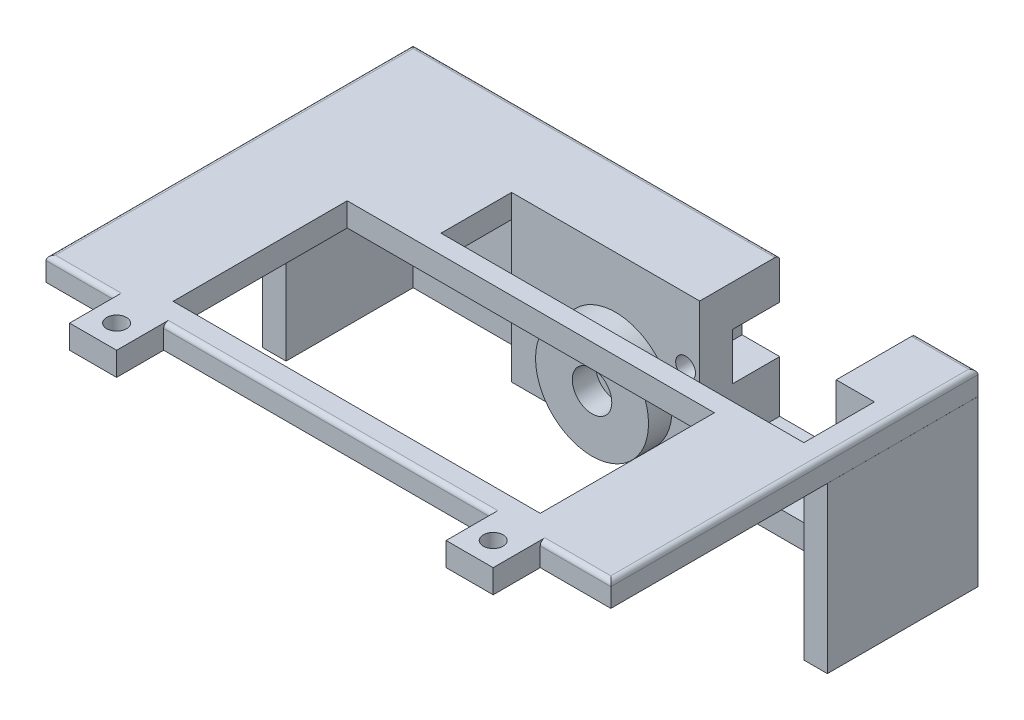
SolidWorks part; units mm, degrees
ref_plane "Спереди" through (0, 0, 0) normal (0, 0, 1) x (1, 0, 0)
ref_plane "Сверху" through (0, 0, 0) normal (0, 1, 0) x (1, 0, 0)
ref_plane "Справа" through (0, 0, 0) normal (1, 0, 0) x (0, 0, -1)
ref_plane "Плоскость4" through (0, 0, 54.0527) normal (0, 0, -1) x (-1, 0, 0)
sketch "Эскиз1" plane through (0, 0, 54.0527) normal (0, 0, -1) x (-1, 0, 0)
  circle A0 centre (-68.7418, 84.0014) radius 4.2
  circle A1 centre (-68.7418, 84.0014) radius 12
extrude "Бобышка-Вытянуть1" add sketch "Эскиз1" along normal blind 5
ref_plane "Плоскость5" through (0, 0, 49.0527) normal (0, 0, -1) x (-1, 0, 0)
sketch "Эскиз2" plane through (0, 0, 49.0527) normal (0, 0, -1) x (-1, 0, 0)
  line L0 (-115.6175, 77.2768) -> (-86.6175, 77.2768)
  line L1 (-86.6175, 93.2768) -> (-86.6175, 102.0014)
  line L2 (-128.7418, 102.0014) -> (-8.7418, 102.0014) construction
  line L3 (-115.6175, 93.2768) -> (-115.6175, 77.2768)
  line L4 (-46.6175, 102.0014) -> (-46.6175, 57.1014)
  line L5 (-86.6175, 93.2768) -> (-86.6175, 77.2768)
  line L6 (-53.8918, 57.1014) -> (-83.5918, 57.1014) construction
  line L7 (-115.6175, 93.2768) -> (-115.6175, 102.0014)
  line L8 (-115.6175, 102.0014) -> (-123.7418, 102.0014)
  line L9 (-86.6175, 102.0014) -> (-46.6175, 102.0014)
  line L10 (-123.7418, 57.1014) -> (-46.6175, 57.1014)
  line L14 (-123.7418, 102.0014) -> (-123.7418, 57.1014)
  line L15 (-123.7418, 67.1014) -> (-123.7418, 57.1014) construction
  circle A0 centre (-118.6175, 93.2768) radius 2
  circle A1 centre (-83.6175, 93.2768) radius 2
extrude "Бобышка-Вытянуть2" add sketch "Эскиз2" along normal blind 5
ref_plane "Плоскость6" through (0, 0, 44.0527) normal (0, 0, -1) x (-1, 0, 0)
sketch "Эскиз3" plane through (0, 0, 44.0527) normal (0, 0, -1) x (-1, 0, 0)
  line L0 (-123.7418, 57.1014) -> (-123.7418, 72.0014)
  line L1 (-123.7418, 102.0014) -> (-123.7418, 57.1014) construction
  line L3 (-123.7418, 72.0014) -> (-46.6175, 72.0014)
  line L4 (-46.6175, 57.1014) -> (-46.6175, 102.0014) construction
  line L5 (-46.6175, 72.0014) -> (-46.6175, 57.1014)
  line L6 (-46.6175, 57.1014) -> (-123.7418, 57.1014)
extrude "Бобышка-Вытянуть3" add sketch "Эскиз3" along normal blind 7
ref_plane "Плоскость8" through (0, 72.0014, 0) normal (0, 1, 0) x (1, 0, 0)
sketch "Эскиз4" plane through (0, 72.0014, 0) normal (0, 1, 0) x (1, 0, 0)
  line L0 (123.7418, -37.0527) -> (13.7418, -37.0527)
  line L1 (13.7418, -37.0527) -> (13.7418, -59.0527)
  line L5 (13.7418, -59.0527) -> (8.7418, -59.0527)
  line L10 (8.7418, -59.0527) -> (8.7418, -32.0527)
  line L12 (128.7418, -17.0527) -> (128.7418, -64.0527) construction
  line L13 (128.7418, -32.0527) -> (128.7418, -59.0527)
  line L14 (128.7418, -59.0527) -> (123.7418, -59.0527)
  line L15 (123.7418, -59.0527) -> (123.7418, -37.0527)
  line L16 (8.7418, -32.0527) -> (128.7418, -32.0527)
extrude "Бобышка-Вытянуть6" add sketch "Эскиз4" along normal blind 30 separate body
sketch "Эскиз5" plane through (0, 0, 44.0527) normal (0, 0, -1) x (-1, 0, 0)
  line L0 (-115.6175, 102.0014) -> (-115.6175, 77.2768)
  line L1 (-115.6175, 77.2768) -> (-115.6175, 102.0014) construction
  line L2 (-115.6175, 77.2768) -> (-86.6175, 77.2768)
  line L3 (-86.6175, 77.2768) -> (-86.6175, 102.0014)
  line L4 (-86.6175, 102.0014) -> (-86.6175, 77.2768) construction
  line L5 (-115.6175, 102.0014) -> (-86.6175, 102.0014)
extrude "Вырез-Вытянуть16" cut sketch "Эскиз5" along normal blind 30
sketch "Эскиз6" plane through (0, 72.0014, 0) normal (0, 1, 0) x (1, 0, 0)
  line L0 (23.7418, -22.0527) -> (33.7418, -22.0527)
  line L1 (33.7418, -22.0527) -> (33.7418, -32.0527)
  line L4 (33.7418, -32.0527) -> (23.7418, -32.0527)
  line L5 (23.7418, -32.0527) -> (23.7418, -22.0527)
  line L6 (103.7418, -22.0527) -> (113.7418, -22.0527)
  line L7 (113.7418, -22.0527) -> (113.7418, -32.0527)
  line L10 (113.7418, -32.0527) -> (103.7418, -32.0527)
  line L11 (103.7418, -32.0527) -> (103.7418, -22.0527)
  circle A0 centre (28.7418, -27.0527) radius 2.1
  circle A1 centre (108.7418, -27.0527) radius 2.1
  point P2 (0, 0)
  point P3 (0, 0)
  point P6 (0, 0)
  point P7 (0, 0)
  point P8 (0, 0)
  point P9 (0, 0)
  point P11 (0, 0)
  point P13 (0, 0)
  point P14 (0, 0)
  point P17 (0, 0)
  point P18 (0, 0)
  point P22 (0, 0)
ref_plane "Плоскость9" through (0, 72.0014, 0) normal (0, 1, 0) x (1, 0, 0)
sketch "Эскиз7" plane through (0, 72.0014, 0) normal (0, 1, 0) x (1, 0, 0)
  line L0 (123.7418, -44.0527) -> (115.6175, -44.0527)
  line L1 (16.5, -44.0527) -> (-16.5, -44.0527) construction
  line L2 (115.6175, -37.0527) -> (123.7418, -37.0527)
  line L3 (123.7418, -37.0527) -> (123.7418, -44.0527)
  line L4 (123.7418, -37.0527) -> (123.7418, -59.0527) construction
  line L5 (115.6175, -44.0527) -> (115.6175, -37.0527)
  line L6 (86.6175, -37.0527) -> (86.6175, -44.0527)
  line L7 (86.6175, -32.0527) -> (86.6175, -37.0527) construction
  line L8 (13.7418, -37.0527) -> (86.6175, -37.0527) construction
  line L9 (86.6175, -44.0527) -> (46.6175, -44.0527)
  line L10 (46.6175, -44.0527) -> (46.6175, -49.0527) construction
  line L11 (46.6175, -44.0527) -> (46.6175, -37.0527)
  line L12 (46.6175, -37.0527) -> (86.6175, -37.0527)
sketch "Эскиз8" plane through (0, 72.0014, 0) normal (0, 1, 0) x (1, 0, 0)
  line L0 (86.6175, -37.0527) -> (86.6175, -44.0527)
  line L1 (16.5, -44.0527) -> (-16.5, -44.0527) construction
  line L2 (86.6175, -44.0527) -> (115.6175, -44.0527)
  line L3 (115.6175, -44.0527) -> (115.6175, -37.0527)
  line L4 (115.6175, -37.0527) -> (86.6175, -37.0527)
sketch "Эскиз9" plane through (0, 0, 49.0527) normal (0, 0, -1) x (-1, 0, 0)
  circle A0 centre (-83.6175, 93.2768) radius 2.1
  circle A1 centre (-118.6175, 93.2768) radius 2
extrude "Вырез-Вытянуть17" cut sketch "Эскиз9" along normal blind 17
extrude "Бобышка-Вытянуть12" add sketch "Эскиз6" along normal blind 5
ref_plane "Плоскость10" through (0, 102.0014, 0) normal (0, 1, 0) x (1, 0, 0)
extrude "Бобышка-Вытянуть26" add sketch "Эскиз7" along normal blind 30 separate body
extrude "Бобышка-Вытянуть29" add sketch "Эскиз8" along normal up to surface (5.2754 mm away) contours L2 L3 L4 L0 up to face at (101.1175, 77.2768, 46.5527)
ref_plane "Плоскость11" through (0, 0, 32.0527) normal (0, 0, -1) x (-1, 0, 0)
sketch "Эскиз18" plane through (0, 0, 32.0527) normal (0, 0, -1) x (-1, 0, 0)
  line L0 (-86.6175, 88.2768) -> (-78.6175, 88.2768)
  line L1 (-78.6175, 88.2768) -> (-78.6175, 98.2768)
  line L2 (-78.6175, 98.2768) -> (-86.6175, 98.2768)
  line L3 (-86.6175, 98.2768) -> (-86.6175, 88.2768)
  line L4 (-115.6175, 88.2768) -> (-123.6175, 88.2768)
  line L5 (-123.6175, 88.2768) -> (-123.6175, 98.4903)
  line L6 (-123.6175, 98.4903) -> (-115.6175, 98.4903)
  line L7 (-115.6175, 98.4903) -> (-115.6175, 88.2768)
sketch "Эскиз16" plane through (0, 0, 49.0527) normal (0, 0, -1) x (-1, 0, 0)
  circle A0 centre (-118.6175, 93.2768) radius 2
  circle A1 centre (-83.6175, 93.2768) radius 2.1
extrude "Вырез-Вытянуть19" cut sketch "Эскиз16" along normal blind 17
extrude "Вырез-Вытянуть20" cut sketch "Эскиз18" against normal blind 10
sketch "Эскиз19" plane through (0, 102.0014, 0) normal (0, 1, 0) x (1, 0, 0)
  line L0 (8.7418, -32.0527) -> (86.6175, -32.0527)
  line L1 (86.6175, -32.0527) -> (8.7418, -32.0527) construction
  line L2 (86.6175, -32.0527) -> (86.6175, -49.0527)
  line L3 (86.6175, -32.0527) -> (86.6175, -49.0527) construction
  line L4 (86.6175, -49.0527) -> (46.6606, -49.0527)
  line L5 (46.6606, -49.0527) -> (46.6606, -64.0527)
  line L6 (128.7418, -64.0527) -> (8.7418, -64.0527) construction
  line L7 (46.6606, -64.0527) -> (123.7418, -64.0527)
  line L9 (123.7418, -64.0527) -> (123.7418, -49.0527)
  line L10 (22.9085, -49.0527) -> (-22.9085, -49.0527) construction
  line L11 (123.7418, -49.0527) -> (115.6175, -49.0527)
  line L12 (115.6175, -32.0527) -> (115.6175, -49.0527) construction
  line L14 (115.6175, -49.0527) -> (115.6175, -32.0527)
  line L15 (27.045, -32.0527) -> (-27.045, -32.0527) construction
  line L16 (115.6175, -32.0527) -> (128.7343, -32.0527)
  line L18 (128.7343, -32.0527) -> (128.7418, -110.0527)
  line L19 (128.7418, -110.0527) -> (113.7418, -110.0527)
  line L20 (113.7418, -110.0527) -> (113.7418, -120.0527)
  line L21 (113.7418, -120.0527) -> (103.7418, -120.0527)
  line L22 (103.7418, -120.0527) -> (103.7418, -110.0527)
  line L23 (103.7418, -110.0527) -> (33.7418, -110.0527)
  line L24 (33.7418, -110.0527) -> (33.7418, -120.0527)
  line L25 (33.7418, -120.0527) -> (23.7418, -120.0527)
  line L26 (23.7418, -120.0527) -> (23.7418, -110.0527)
  line L27 (23.7418, -110.0527) -> (8.7418, -110.0527)
  line L28 (8.7418, -110.0527) -> (8.7418, -32.0527)
  line L29 (30.7407, -68.0527) -> (30.7418, -105.0527)
  line L30 (62.1968, -68.0527) -> (75.2868, -68.0527) construction
  line L31 (76.9629, -105.0527) -> (60.5207, -105.0527) construction
  line L32 (30.7418, -105.0527) -> (30.7418, -110.0527) construction
  line L33 (30.7418, -105.0527) -> (108.7418, -105.0527)
  line L34 (108.7418, -104.0527) -> (108.7418, -110.0527) construction
  line L35 (108.7418, -105.0527) -> (108.7418, -68.0527)
  line L36 (108.7418, -69.0527) -> (108.7418, -64.0527) construction
  line L37 (108.7418, -68.0527) -> (30.7407, -68.0527)
  circle A0 centre (28.7418, -115.0527) radius 2.1
  circle A1 centre (108.7418, -115.0527) radius 2.1
extrude "Бобышка-Вытянуть34" add sketch "Эскиз19" along normal blind 5
fillet "Скругление1" radius 1 7 edges at (16.2418, 107.0014, 110.0527) (68.7418, 107.0014, 110.0527) (121.2418, 107.0014, 110.0527) (128.738, 107.0014, 71.0527) (122.1759, 107.0014, 32.0527) (47.6796, 107.0014, 32.0527) (8.7418, 107.0014, 71.0527)
ref_plane "Плоскость12" through (0, 57.1014, 0) normal (0, -1, 0) x (-1, 0, 0)
sketch "Эскиз20" plane through (0, 57.1014, 0) normal (0, -1, 0) x (-1, 0, 0)
  line L7 (22.9085, -49.0527) -> (-22.9085, -49.0527) construction
  line L8 (-123.7418, -37.0527) -> (-46.6175, -37.0527)
  line L9 (-123.7418, -37.0527) -> (-123.7418, -49.0527)
  line L10 (-123.7418, -49.0527) -> (-46.6175, -49.0527)
  line L11 (-46.6175, -37.0527) -> (-46.6175, -49.0527)
extrude "Вырез-Вытянуть22" cut sketch "Эскиз20" against normal blind 15
ref_plane "Плоскость13" through (0, 72.0014, 0) normal (0, -1, 0) x (-1, 0, 0)
sketch "Эскиз21" plane through (0, 72.0014, 0) normal (0, -1, 0) x (-1, 0, 0)
  line L0 (-128.7418, -59.0527) -> (-123.7418, -59.0527)
  line L1 (-123.7418, -59.0527) -> (-128.7418, -59.0527) construction
  line L2 (-128.7418, -59.0527) -> (-128.7418, -32.0527) construction
  line L10 (-13.7418, -59.0527) -> (-13.7418, -37.0527) construction
  line L11 (-13.7418, -37.0527) -> (-123.7418, -37.0527) construction
  line L12 (-13.7418, -37.0527) -> (-13.7418, -59.0527)
  line L13 (-13.7418, -59.0527) -> (-8.7418, -59.0527)
  line L14 (-8.7418, -59.0527) -> (-8.7418, -32.0527)
  line L15 (27.045, -32.0527) -> (-27.045, -32.0527) construction
  line L16 (-8.7418, -125.0527) -> (-8.7418, -17.0527) construction
  line L17 (-8.7418, -32.0527) -> (-23.7418, -32.0527)
  line L18 (-23.7418, -22.0527) -> (-23.7418, -32.0527) construction
  line L19 (-23.7418, -32.0527) -> (-23.7418, -22.0527)
  line L20 (-23.7418, -22.0527) -> (-33.7418, -22.0527)
  line L21 (-33.7418, -22.0527) -> (-33.7418, -32.0527)
  line L22 (-33.7418, -32.0527) -> (-33.7418, -22.0527) construction
  line L23 (-33.7418, -32.0527) -> (-103.7418, -32.0527)
  line L24 (-103.7418, -22.0527) -> (-103.7418, -32.0527) construction
  line L25 (-103.7418, -32.0527) -> (-103.7418, -22.0527)
  line L26 (-113.7418, -22.0527) -> (-103.7418, -22.0527) construction
  line L27 (-103.7418, -22.0527) -> (-113.7418, -22.0527)
  line L28 (-113.7418, -22.0527) -> (-113.7418, -32.0527)
  line L29 (-113.7418, -32.0527) -> (-128.7418, -32.0527)
  line L30 (-128.7418, -125.0527) -> (-128.7418, -17.0527) construction
  line L31 (-128.7418, -32.0527) -> (-128.7418, -59.0527)
  line L32 (-123.7418, -59.0527) -> (-123.7418, -37.0527)
  line L33 (-123.7418, -37.0527) -> (-13.7418, -37.0527)
  circle A0 centre (-108.7418, -27.0527) radius 2.1
  circle A1 centre (-28.7418, -27.0527) radius 2.1
extrude "Бобышка-Вытянуть38" add sketch "Эскиз21" along normal blind 5
ref_plane "Плоскость14" through (0, 0, 59.0527) normal (0, 0, 1) x (1, 0, 0)
sketch "Эскиз22" plane through (0, 0, 59.0527) normal (0, 0, 1) x (1, 0, 0)
  line L0 (8.7422, 102.0014) -> (13.7418, 102.0014)
  line L2 (54.6117, 102.0014) -> (-54.6117, 102.0014) construction
  line L3 (13.7418, 102.0014) -> (13.7418, 67.0014)
  line L4 (13.7418, 67.0014) -> (8.7418, 67.0014)
  line L5 (8.7418, 67.0014) -> (8.7422, 102.0014)
  line L11 (123.7418, 107.0014) -> (123.7418, 102.0014) construction
  line L12 (123.7418, 102.0014) -> (128.7418, 102.0014)
  line L14 (123.7418, 102.0014) -> (123.7418, 67.0014)
  line L15 (123.7418, 67.1014) -> (123.7418, 57.1014) construction
  line L16 (128.7418, 67.0014) -> (123.7418, 67.0014) construction
  line L17 (123.7418, 67.0014) -> (128.7418, 67.0014)
  line L18 (128.7418, 67.0014) -> (128.7418, 102.0014)
extrude "Бобышка-Вытянуть39" add sketch "Эскиз22" along normal blind 5
